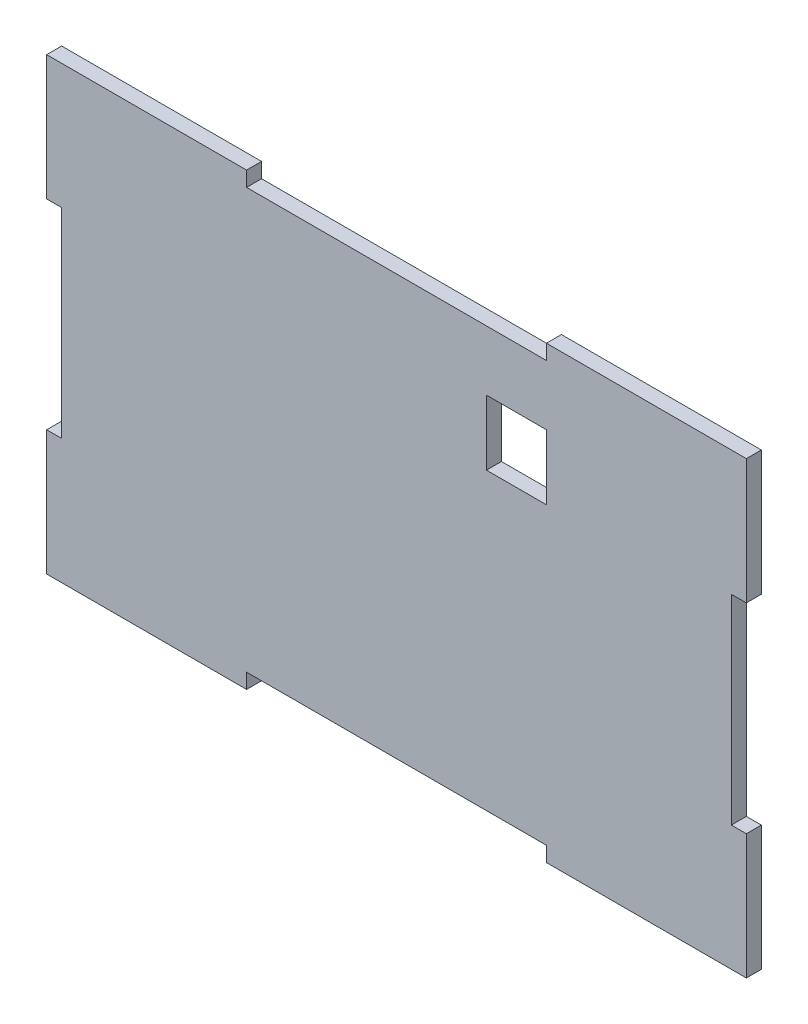
SolidWorks part; units mm, degrees
ref_plane "Спереди" through (0, 0, 0) normal (0, 0, 1) x (1, 0, 0)
ref_plane "Сверху" through (0, 0, 0) normal (0, 1, 0) x (1, 0, 0)
ref_plane "Справа" through (0, 0, 0) normal (1, 0, 0) x (0, 0, -1)
other "Configuration Table"
sketch "Эскиз1" plane through (0, 0, 0) normal (0, 0, 1) x (1, 0, 0)
  line L0 (70, 0) -> (70, 90) construction
  line L1 (0, 0) -> (40, 0)
  line L2 (0, 0) -> (0, 25)
  line L5 (0, 45) -> (140, 45) construction
  line L6 (40, 0) -> (40, 3)
  line L7 (40, 3) -> (100, 3)
  line L8 (137, 25) -> (137, 65)
  line L10 (0, 25) -> (3, 25)
  line L11 (3, 25) -> (3, 65)
  line L12 (140, 25) -> (137, 25)
  line L14 (100, 0) -> (100, 3)
  line L15 (140, 0) -> (140, 25)
  line L16 (140, 0) -> (100, 0)
  line L18 (140, 90) -> (100, 90)
  line L19 (140, 90) -> (140, 65)
  line L20 (100, 90) -> (100, 87)
  line L21 (140, 65) -> (137, 65)
  line L22 (0, 65) -> (3, 65)
  line L23 (40, 87) -> (100, 87)
  line L24 (40, 90) -> (40, 87)
  line L25 (0, 90) -> (0, 65)
  line L26 (0, 90) -> (40, 90)
  point P15 (1.5, 25)
  point P21 (70, 3)
  point P27 (3, 45)
  point P28 (137, 45)
  point P30 (70, 87)
  point P31 (100, 88.5)
  dimension "D1" = 90
  dimension "D2" = 140
  dimension "D3" = 25
  dimension "D4" = 3
  dimension "D5" = 40
  dimension "D6" = 3
  dimension "D7" = 40
  dimension "D8" = 60
extrude "Бобышка-Вытянуть1" add sketch "Эскиз1" along normal blind 3
sketch "Эскиз2" plane through (0, 0, 3) normal (0, 0, 1) x (1, 0, 0)
  line L0 (0, 90) -> (0, 65) construction
  line L1 (88, 75) -> (100, 75)
  line L2 (88, 75) -> (88, 62)
  line L3 (88, 62) -> (100, 62)
  line L4 (100, 75) -> (100, 62)
  line L5 (100, 0) -> (140, 0) construction
  line L6 (100, 87) -> (40, 87) construction
  dimension "D1" = 88
  dimension "D2" = 12
  dimension "D3" = 62
  dimension "D4" = 13
  dimension "D5" = 12
extrude "Вырез-Вытянуть1" cut sketch "Эскиз2" against normal through all
